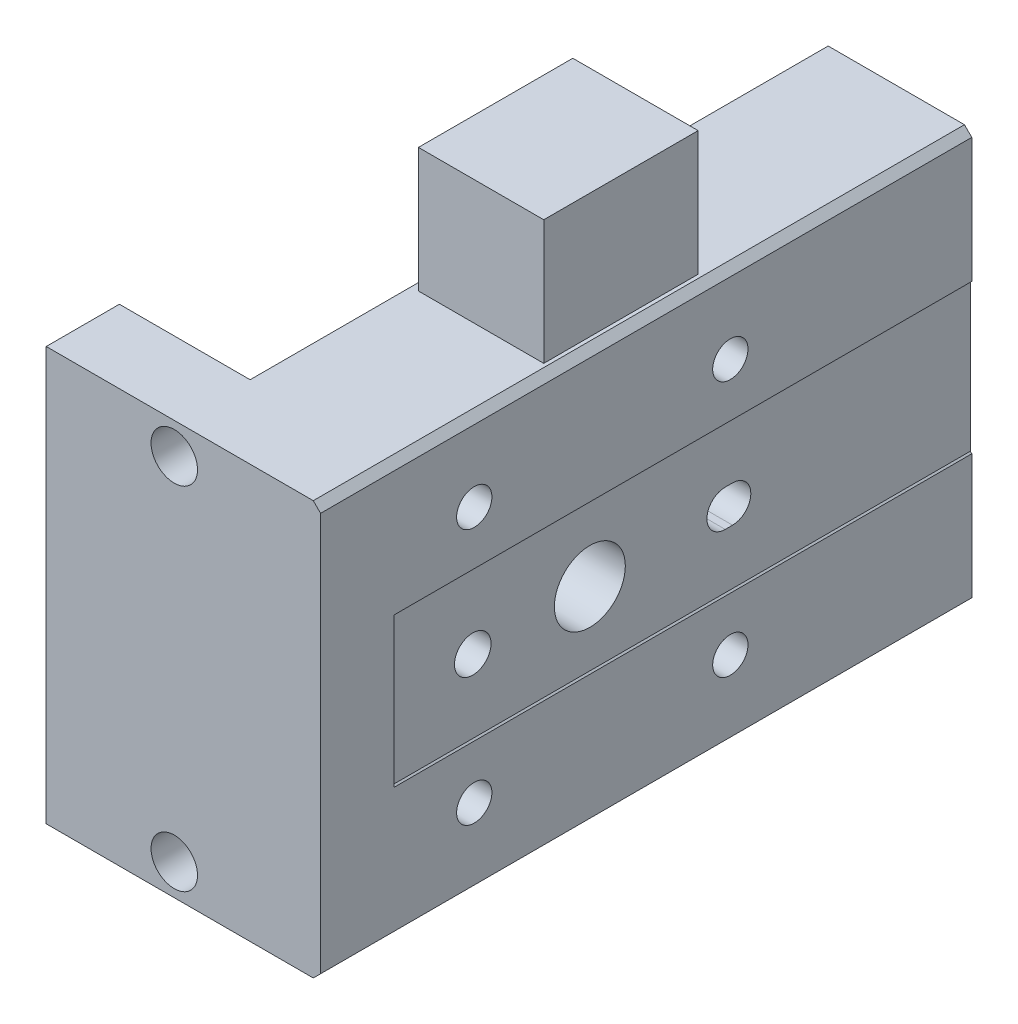
SolidWorks part; units mm, degrees
ref_plane "Front" through (0, 0, 0) normal (0, 0, 1) x (1, 0, 0)
ref_plane "Top" through (0, 0, 0) normal (0, 1, 0) x (1, 0, 0)
ref_plane "Right" through (0, 0, 0) normal (1, 0, 0) x (0, 0, -1)
sketch "Sketch1" plane through (0, 0, -1145.0127) normal (0, 0, 1) x (1, 0, 0)
  line L0 (9.5504, 28.25) -> (8.1854, 28.25) construction
  line L1 (-7.6854, 28.25) -> (29.8146, 28.25)
  line L2 (-7.6854, 28.25) -> (-7.6854, -28.25)
  line L3 (-7.6854, -28.25) -> (29.8146, -28.25)
  line L4 (29.8146, 28.25) -> (29.8146, 10.2)
  line L5 (-7.6854, 0) -> (29.6146, 0) construction
  line L6 (-10.1854, 27.615) -> (-10.1854, 8.763) construction
  line L8 (-2.3749, -28.25) -> (2.3749, -28.25) construction
  line L9 (29.6146, 10) -> (29.6146, -10)
  line L10 (29.6146, -10) -> (29.8146, -10.2)
  line L11 (29.6146, 10) -> (29.8146, 10.2)
  line L12 (29.8146, -10.2) -> (29.8146, -28.25)
  dimension "D1" = 2.5
  dimension "D2" = 40
  dimension "D3" = 45
  dimension "D4" = 0.2
  dimension "D5" = 20
extrude "Base-Extrude" add sketch "Sketch1" along normal up to surface (10 mm away)
sketch "Sketch3" plane through (0, 0, -1145.0127) normal (0, 0, -1) x (-1, 0, 0)
  line L0 (-29.8146, 10.2) -> (-29.8146, 28.25) construction
  line L1 (-29.8146, 28.25) -> (7.6854, 28.25) construction
  line L2 (-29.8146, 10.2) -> (-29.8146, 28.25)
  line L3 (-29.8146, 28.25) -> (-10.1854, 28.25)
  line L4 (7.6854, -28.25) -> (-29.8146, -28.25) construction
  line L5 (-29.8146, -28.25) -> (-29.8146, -10.2) construction
  line L6 (-29.8146, -10.2) -> (-29.6146, -10) construction
  line L7 (-29.6146, -10) -> (-29.6146, 10) construction
  line L8 (-29.6146, 10) -> (-29.8146, 10.2) construction
  line L9 (-10.1854, -28.25) -> (-29.8146, -28.25)
  line L10 (-29.8146, -28.25) -> (-29.8146, -10.2)
  line L11 (-29.8146, -10.2) -> (-29.6146, -10)
  line L12 (-29.6146, -10) -> (-29.6146, 10)
  line L13 (-29.6146, 10) -> (-29.8146, 10.2)
  line L14 (-10.1854, -8.763) -> (-10.1854, -27.615) construction
  line L19 (-10.1854, 28.25) -> (-10.1854, -28.25)
extrude "Boss-Extrude1" add sketch "Sketch3" along normal up to surface (79 mm away)
sketch "Sketch15" plane through (0, 0, -1135.0127) normal (0, 0, 1) x (1, 0, 0)
  line L0 (29.8146, -10.2) -> (29.6146, -10) construction
  line L1 (29.6146, 10) -> (29.8146, 10.2) construction
  line L2 (29.6146, -10) -> (29.6146, 10) construction
  line L3 (29.8146, -10.2) -> (29.6146, -10)
  line L4 (29.6146, 10) -> (29.8146, 10.2)
  line L5 (29.6146, -10) -> (29.6146, 10)
  line L6 (29.8146, -10.2) -> (29.8146, 10.2)
extrude "Boss-Extrude3" add sketch "Sketch15" against normal up to surface (10 mm away) up to face at (1.25, -7.0625, -1145.0127)
hole_wizard "9.7 Diameter Hole1" positions "Sketch5" profile "Sketch4" hole size "M9.7" standard "Ansi Metric" end condition through all
sketch "Sketch5" plane through (29.6146, 0, 0) normal (1, 0, 0) x (0, 0, -1)
  point P0 (1172.0127, 0)
sketch "Sketch4" plane through (29.6146, 0, -1172.0127) normal (0, 1, 0) x (0, 0, -1)
  line L0 (0, 0) -> (0, 37.3)
  line L1 (0, 37.3) -> (4.85, 37.3)
  line L2 (4.85, 37.3) -> (4.85, 0)
  line L5 (4.85, 0) -> (0, 0)
  line L11 (0, -6.35) -> (0, 107.95) construction
  dimension "Thru Hole Dia." = 9.7
  dimension "Thru Hole Depth" = 37.3
hole_wizard "#10-32 Tapped Hole1" positions "Sketch7" profile "Sketch6" tap size "#10-32" standard "Ansi Inch"
sketch "Sketch7" plane through (29.8146, 0, 0) normal (1, 0, 0) x (0, 0, -1)
  point P0 (1156.0127, 17.5)
  point P1 (1191.0127, 17.5)
  point P3 (1156.0127, -17.5)
  point P4 (1191.0127, -17.5)
sketch "Sketch6" plane through (29.8146, 17.5, -1156.0127) normal (0, 1, 0) x (0, 0, -1)
  line L0 (0, 0) -> (0, 14.0757)
  line L1 (0, 14.0757) -> (2.0193, 12.8624)
  line L2 (2.0193, 12.8624) -> (2.0193, 8.9)
  line L3 (2.0193, 8.9) -> (2.413, 8.9)
  line L4 (2.413, 8.9) -> (2.413, 0)
  line L5 (2.413, 0) -> (0, 0)
  line L10 (0, 14.0757) -> (-2.0193, 12.8624) construction
  line L11 (0, -6.35) -> (0, 107.95) construction
  dimension "Tap Drill Dia." = 4.0386
  dimension "Tap Drill Depth" = 12.8624
  dimension "Thread Dia." = 4.826
  dimension "Thread Depth" = 8.9
  dimension "Drill Angle" = 118
hole_wizard "1/4-20 Tapped Hole1" positions "Sketch10" profile "Sketch9" tap size "1/4-20" standard "Ansi Inch"
sketch "Sketch10" plane through (0, 0, -1135.0127) normal (0, 0, 1) x (1, 0, 0)
  line L0 (-10.1854, 27.615) -> (-10.1854, 8.763) construction
  line L1 (-9.5504, 0) -> (9.8146, 0) construction
  line L2 (-9.5504, 8.128) -> (-9.5504, -8.128) construction
  point P0 (9.8146, 24)
  point P1 (9.8146, -24)
  dimension "D1" = 20
  dimension "D2" = 48
sketch "Sketch9" plane through (9.8146, 24, -1135.0127) normal (1, 0, 0) x (0, -1, 0)
  line L0 (0, 0) -> (0, 10)
  line L1 (0, 10) -> (3.175, 10)
  line L2 (3.175, 10) -> (3.175, 0)
  line L5 (3.175, 0) -> (0, 0)
  line L11 (0, -6.35) -> (0, 107.95) construction
  dimension "Thru Hole Dia." = 6.35
  dimension "Thru Hole Depth" = 10
sketch "Sketch11" plane through (29.6146, 0, 0) normal (1, 0, 0) x (0, 0, -1)
  line L0 (1191.0127, 17.5) -> (1191.0127, 0) construction
  line L2 (1135.0127, 0) -> (1224.0127, 0) construction
  line L4 (1194.0127, 0) -> (1194.0127, 17.5) construction
  line L5 (1188.0127, 0) -> (1188.0127, 17.5) construction
  line L6 (1190.5127, 2.5) -> (1191.5127, 2.5)
  line L7 (1190.5127, -2.5) -> (1191.5127, -2.5)
  arc A0 (1191.5127, -2.5) -> (1191.5127, 2.5) centre (1191.5127, 0) ccw
  arc A1 (1190.5127, 2.5) -> (1190.5127, -2.5) centre (1190.5127, 0) ccw
  dimension "D1" = 5
  dimension "D2" = 6
extrude "Cut-Extrude1" cut sketch "Sketch11" against normal blind 4
hole_wizard "Hole1" positions "Sketch13" profile "Sketch12" legacy
sketch "Sketch13" plane through (29.6146, 0, 0) normal (1, 0, 0) x (0, 0, -1)
  line L0 (1135.0127, 0) -> (1224.0127, 0) construction
  point P0 (1156.0127, 0)
sketch "Sketch12" plane through (29.6146, 0, -1156.0127) normal (0, 1, 0) x (0, 0, -1)
  line L0 (0, 0) -> (0, 4)
  line L1 (0, 4) -> (2.5, 4)
  line L2 (2.5, 4) -> (2.5, 0)
  line L3 (2.5, 0) -> (0, 0)
  line L4 (0, 110) -> (0, -10) construction
  dimension "Diameter" = 5
  dimension "Depth" = 4
sketch "Sketch2" plane through (0, 0, -1135.0127) normal (0, 0, 1) x (1, 0, 0)
  line L0 (29.8146, -28.25) -> (29.8146, 28.25) construction
  circle A2 centre (0, 13.5128) radius 3
  circle A3 centre (0, -14.859) radius 3
  circle A4 centre (21.8146, 20) radius 4
  circle A5 centre (21.8146, -20) radius 4
  dimension "D1" = 8
  dimension "D4" = 6
  dimension "D3" = 8
sketch "Sketch14" plane through (0, 28.25, 0) normal (0, 1, 0) x (-1, 0, 0)
  line L1 (-28.3146, -1167.0127) -> (-11.1854, -1167.0127)
  line L2 (-28.3146, -1167.0127) -> (-28.3146, -1188.1127)
  line L3 (-28.3146, -1188.1127) -> (-11.1854, -1188.1127)
  line L4 (-11.1854, -1167.0127) -> (-11.1854, -1188.1127)
  line L5 (-29.8146, -1135.0127) -> (-29.8146, -1224.0127) construction
  line L6 (-10.1854, -1224.0127) -> (-10.1854, -1145.0127) construction
  line L7 (-8.925, -1167.0127) -> (8.925, -1167.0127) construction
  dimension "D1" = 21.1
  dimension "D3" = 1.5
  dimension "D4" = 1
extrude "Boss-Extrude2" add sketch "Sketch14" along normal blind 17
chamfer "Chamfer1" distance 1 angle 45 2 edges at (29.8146, 28.25, -1179.5127) (29.8146, -28.25, -1179.5127)
